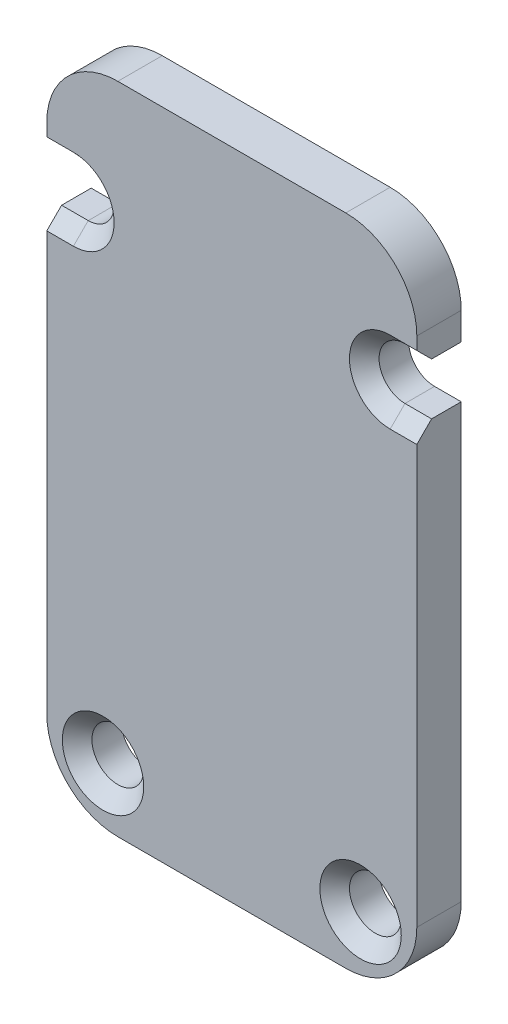
SolidWorks part; units mm, degrees
ref_plane "Płaszczyzna przednia" through (0, 0, 0) normal (0, 0, 1) x (1, 0, 0)
ref_plane "Płaszczyzna górna" through (0, 0, 0) normal (0, 1, 0) x (1, 0, 0)
ref_plane "Płaszczyzna prawa" through (0, 0, 0) normal (1, 0, 0) x (0, 0, -1)
sketch "Szkic1" plane through (0, 0, 0) normal (0, 0, 1) x (1, 0, 0)
  line L0 (-12.5, -22.1) -> (-12.5, 22.1)
  line L1 (-12.7, -22.3) -> (12.7, -22.3)
  line L2 (-12.7, -22.3) -> (-12.7, 22.3)
  line L3 (-12.7, 22.3) -> (12.7, 22.3)
  line L4 (12.7, -22.3) -> (12.7, 22.3)
  line L5 (-12.7, -22.3) -> (12.7, 22.3) construction
  line L6 (-12.7, 22.3) -> (12.7, -22.3) construction
  line L7 (-12.5, 22.1) -> (12.5, 22.1)
  line L8 (12.5, -22.1) -> (12.5, 22.1)
  line L9 (-12.5, -22.1) -> (12.5, -22.1)
  point P0 (0, 0)
  dimension "D1" = 44.6
  dimension "D2" = 25.4
  dimension "D3" = 0.2
extrude "Dodanie-wyciągnięcie1" add sketch "Szkic1" along normal blind 3 contours L0 L9 L8 L7
fillet "Zaokrąglenie1" radius 4.8 4 edges at (-12.5, -22.1, 1.5) (12.5, -22.1, 1.5) (-12.5, 22.1, 1.5) (12.5, 22.1, 1.5)
sketch "Szkic2" plane through (0, 0, 3) normal (0, 0, 1) x (1, 0, 0)
  line L0 (-12.7, -22.3) -> (12.7, -22.3) construction
  line L1 (0, -22.3) -> (0, 22.3) construction
  line L2 (12.7, 22.3) -> (-12.7, 22.3) construction
  line L3 (-10.7, 15.45) -> (-12.7, 15.45)
  line L4 (-12.7, 22.3) -> (-12.7, -22.3) construction
  line L5 (-12.7, 15.45) -> (-12.7, 11.95)
  line L6 (-12.7, 11.95) -> (-10.7, 11.95)
  line L7 (10.7, 11.95) -> (12.7, 11.95)
  line L8 (12.7, -22.3) -> (12.7, 22.3) construction
  line L9 (12.7, 11.95) -> (12.7, 15.45)
  line L10 (12.7, 15.45) -> (10.7, 15.45)
  circle A0 centre (-8.7, -18.3) radius 1.75
  circle A1 centre (8.7, -18.3) radius 1.75
  circle A2 centre (10.7, 13.7) radius 1.75
  circle A3 centre (-10.7, 13.7) radius 1.75
  dimension "D1" = 17.4
  dimension "D5" = 3.5
  dimension "D2" = 21.4
  dimension "D3" = 4
  dimension "D4" = 32
extrude "Wytnij-wyciągnięcie1" cut sketch "Szkic2" against normal blind 3
chamfer "Sfazowanie1" distance 1 angle 45 8 edges at (-6.95, -18.3, 3) (10.45, -18.3, 3) (11.6, 15.45, 3) (11.6, 11.95, 3) (8.95, 13.7, 3) (-11.6, 11.95, 3) (-11.6, 15.45, 3) (-8.95, 13.7, 3)
